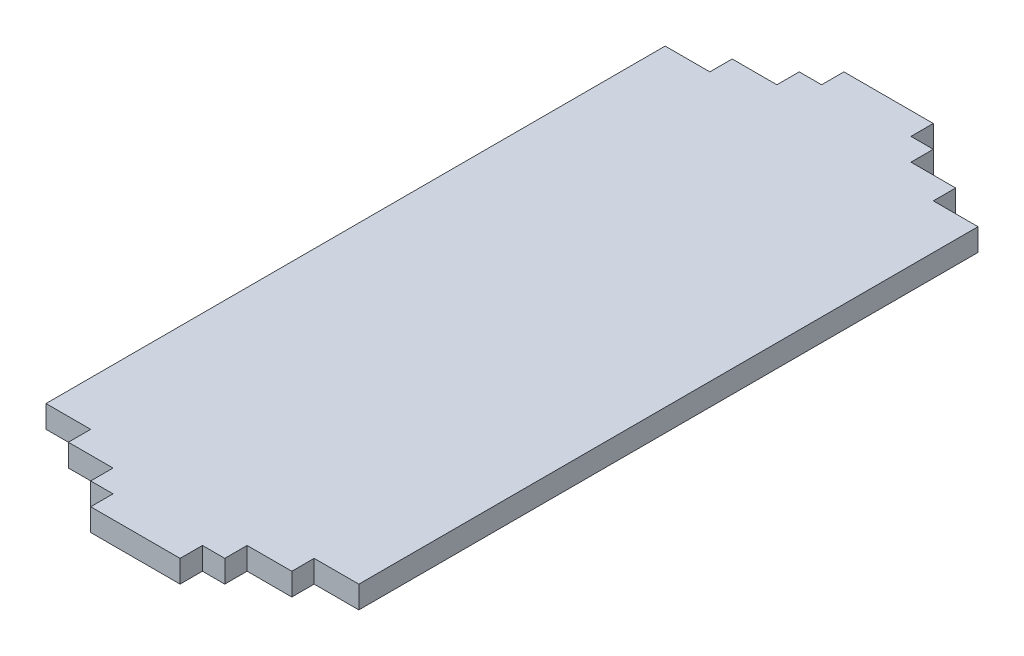
SolidWorks part; units mm, degrees
ref_plane "Front Plane" through (0, 0, 0) normal (0, 0, 1) x (1, 0, 0)
ref_plane "Top Plane" through (0, 0, 0) normal (0, 1, 0) x (1, 0, 0)
ref_plane "Right Plane" through (0, 0, 0) normal (1, 0, 0) x (0, 0, -1)
sketch "Sketch1" plane through (0, 0, 0) normal (0, 0, 1) x (1, 0, 0)
  line L1 (-228.4127, 36.0517) -> (-183.9627, 36.0517)
  line L2 (-228.4127, 36.0517) -> (-228.4127, 32.8767)
  line L3 (-228.4127, 32.8767) -> (-183.9627, 32.8767)
  line L4 (-183.9627, 36.0517) -> (-183.9627, 32.8767)
  dimension "D1" = 3.175
  dimension "D2" = 44.45
extrude "Boss-Extrude1" add sketch "Sketch1" against normal up to vertex (107.0225 mm away) contours L1 L4 L3 L2
sketch "Sketch2" plane through (0, 36.0517, 0) normal (0, 1, 0) x (1, 0, 0)
  line L0 (-286.1582, 97.4975) -> (-45.7559, 97.4975) construction
  line L1 (-228.4127, 107.0225) -> (-222.0627, 107.0225)
  line L2 (-228.4127, 107.0225) -> (-228.4127, 97.4975)
  line L3 (-228.4127, 97.4975) -> (-222.0627, 97.4975)
  line L4 (-222.0627, 100.6725) -> (-222.0627, 97.4975)
  line L5 (-45.7559, 100.6725) -> (-286.1582, 100.6725) construction
  line L6 (-183.9627, 107.0225) -> (-190.3127, 107.0225)
  line L7 (-183.9627, 107.0225) -> (-183.9627, 97.4975)
  line L8 (-183.9627, 97.4975) -> (-190.3127, 97.4975)
  line L9 (-190.3127, 100.6725) -> (-190.3127, 97.4975)
  line L10 (-190.3127, 107.0225) -> (-196.6627, 107.0225)
  line L12 (-190.3127, 100.6725) -> (-196.6627, 100.6725)
  line L13 (-196.6627, 103.8475) -> (-196.6627, 100.6725)
  line L14 (-75.1216, 103.8475) -> (-273.4448, 103.8475) construction
  line L15 (-222.0627, 107.0225) -> (-215.7127, 107.0225)
  line L17 (-222.0627, 100.6725) -> (-215.7127, 100.6725)
  line L18 (-215.7127, 103.8475) -> (-215.7127, 100.6725)
  line L19 (-215.7127, 107.0225) -> (-212.5377, 107.0225)
  line L21 (-215.7127, 103.8475) -> (-212.5377, 103.8475)
  line L22 (-212.5377, 107.0225) -> (-212.5377, 103.8475)
  line L23 (-45.7559, 9.525) -> (-286.1582, 9.525) construction
  line L24 (-196.6627, 107.0225) -> (-199.8377, 107.0225)
  line L26 (-196.6627, 103.8475) -> (-199.8377, 103.8475)
  line L27 (-199.8377, 107.0225) -> (-199.8377, 103.8475)
  line L28 (-228.4127, 0) -> (-222.0627, 0)
  line L29 (-228.4127, 0) -> (-228.4127, 9.525)
  line L30 (-228.4127, 9.525) -> (-222.0627, 9.525)
  line L31 (-222.0627, 6.35) -> (-222.0627, 9.525)
  line L32 (-286.1582, 6.35) -> (-45.7559, 6.35) construction
  line L33 (-222.0627, 0) -> (-215.7127, 0)
  line L35 (-222.0627, 6.35) -> (-215.7127, 6.35)
  line L36 (-215.7127, 3.175) -> (-215.7127, 6.35)
  line L37 (-273.4448, 3.175) -> (-75.1216, 3.175) construction
  line L38 (-215.7127, 0) -> (-212.5377, 0)
  line L40 (-215.7127, 3.175) -> (-212.5377, 3.175)
  line L41 (-212.5377, 0) -> (-212.5377, 3.175)
  line L43 (-183.9627, 0) -> (-190.3127, 0)
  line L44 (-183.9627, 0) -> (-183.9627, 9.525)
  line L45 (-183.9627, 9.525) -> (-190.3127, 9.525)
  line L46 (-190.3127, 6.35) -> (-190.3127, 9.525)
  line L47 (-190.3127, 0) -> (-196.6627, 0)
  line L49 (-190.3127, 6.35) -> (-196.6627, 6.35)
  line L50 (-196.6627, 3.175) -> (-196.6627, 6.35)
  line L51 (-196.6627, 0) -> (-199.8377, 0)
  line L53 (-196.6627, 3.175) -> (-199.8377, 3.175)
  line L54 (-199.8377, 0) -> (-199.8377, 3.175)
  dimension "D1" = 6.35
  dimension "D2" = 6.35
  dimension "D3" = 3.175
  dimension "D4" = 6.35
  dimension "D5" = 6.35
  dimension "D6" = 3.175
  dimension "D7" = 6.35
  dimension "D8" = 6.35
  dimension "D9" = 3.175
  dimension "D10" = 6.35
  dimension "D11" = 6.35
  dimension "D12" = 3.175
extrude "Cut-Extrude1" cut sketch "Sketch2" against normal through all
